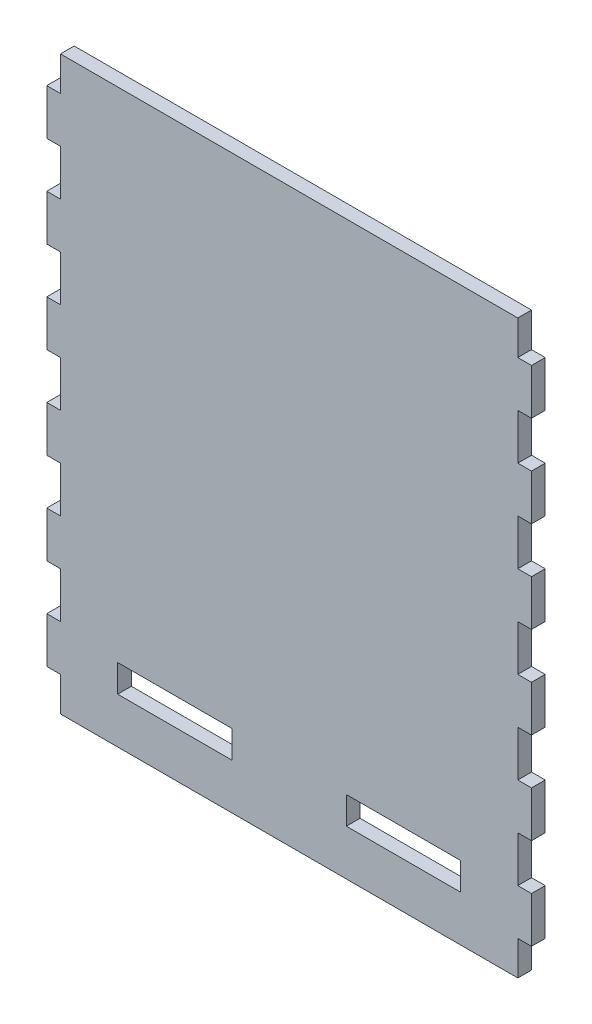
SolidWorks part; units mm, degrees
ref_plane "前视基准面" through (0, 0, 0) normal (0, 0, 1) x (1, 0, 0)
ref_plane "上视基准面" through (0, 0, 0) normal (0, 1, 0) x (1, 0, 0)
ref_plane "右视基准面" through (0, 0, 0) normal (1, 0, 0) x (0, 0, -1)
sketch "草图1" plane through (0, 0, 0) normal (0, 0, 1) x (1, 0, 0)
  line L0 (-118.4309, 110.0336) -> (-118.4309, 90.0336)
  line L1 (-118.4309, 145.0336) -> (81.5691, 145.0336)
  line L2 (-118.4309, 70.0336) -> (-118.4309, 50.0336)
  line L3 (-118.4309, 30.0336) -> (-118.4309, 10.0336)
  line L4 (-118.4309, -9.9664) -> (-118.4309, -29.9664)
  line L5 (-118.4309, -49.9664) -> (-118.4309, -69.9664)
  line L6 (-118.4309, -89.9664) -> (-118.4309, -104.9664)
  line L7 (81.5691, 110.0336) -> (81.5691, 90.0336)
  line L8 (81.5691, 70.0336) -> (81.5691, 50.0336)
  line L9 (81.5691, 30.0336) -> (81.5691, 10.0336)
  line L10 (81.5691, -9.9664) -> (81.5691, -29.9664)
  line L11 (81.5691, -49.9664) -> (81.5691, -69.9664)
  line L12 (81.5691, -89.9664) -> (81.5691, -104.9664)
  line L15 (-43.4309, -84.9664) -> (-93.4309, -84.9664)
  line L16 (-43.4309, -72.9664) -> (-93.4309, -72.9664)
  line L17 (-43.4309, -84.9664) -> (-43.4309, -72.9664)
  line L18 (-93.4309, -72.9664) -> (-93.4309, -84.9664)
  line L20 (6.5691, -84.9664) -> (6.5691, -72.9664)
  line L21 (6.5691, -72.9664) -> (56.5691, -72.9664)
  line L22 (56.5691, -72.9664) -> (56.5691, -84.9664)
  line L23 (-118.4309, -104.9664) -> (81.5691, -104.9664)
  line L24 (56.5691, -84.9664) -> (6.5691, -84.9664)
  line L50 (87.5691, 50.0336) -> (87.5691, 30.0336)
  line L51 (87.5691, 30.0336) -> (81.5691, 30.0336)
  line L53 (81.5691, 50.0336) -> (87.5691, 50.0336)
  line L54 (87.5691, -49.9664) -> (87.5691, -29.9664)
  line L55 (87.5691, 70.0336) -> (81.5691, 70.0336)
  line L57 (81.5691, 90.0336) -> (87.5691, 90.0336)
  line L58 (87.5691, -89.9664) -> (87.5691, -69.9664)
  line L59 (87.5691, 110.0336) -> (81.5691, 110.0336)
  line L61 (81.5691, 130.0336) -> (87.5691, 130.0336)
  line L62 (87.5691, 130.0336) -> (87.5691, 110.0336)
  line L63 (87.5691, 90.0336) -> (87.5691, 70.0336)
  line L64 (81.5691, -89.9664) -> (87.5691, -89.9664)
  line L66 (87.5691, -69.9664) -> (81.5691, -69.9664)
  line L67 (81.5691, -49.9664) -> (87.5691, -49.9664)
  line L69 (87.5691, -29.9664) -> (81.5691, -29.9664)
  line L70 (81.5691, -9.9664) -> (87.5691, -9.9664)
  line L72 (87.5691, 10.0336) -> (81.5691, 10.0336)
  line L73 (87.5691, -9.9664) -> (87.5691, 10.0336)
  line L74 (-124.4309, -9.9664) -> (-124.4309, 10.0336)
  line L75 (-124.4309, 10.0336) -> (-118.4309, 10.0336)
  line L77 (-118.4309, -9.9664) -> (-124.4309, -9.9664)
  line L78 (-124.4309, -29.9664) -> (-118.4309, -29.9664)
  line L80 (-118.4309, -49.9664) -> (-124.4309, -49.9664)
  line L81 (-124.4309, -69.9664) -> (-118.4309, -69.9664)
  line L83 (-118.4309, -89.9664) -> (-124.4309, -89.9664)
  line L84 (-124.4309, 90.0336) -> (-124.4309, 70.0336)
  line L85 (-124.4309, 130.0336) -> (-124.4309, 110.0336)
  line L86 (-118.4309, 130.0336) -> (-124.4309, 130.0336)
  line L88 (-124.4309, 110.0336) -> (-118.4309, 110.0336)
  line L89 (-124.4309, -89.9664) -> (-124.4309, -69.9664)
  line L90 (-118.4309, 90.0336) -> (-124.4309, 90.0336)
  line L92 (-124.4309, 70.0336) -> (-118.4309, 70.0336)
  line L93 (-124.4309, -49.9664) -> (-124.4309, -29.9664)
  line L94 (-118.4309, 50.0336) -> (-124.4309, 50.0336)
  line L96 (-124.4309, 30.0336) -> (-118.4309, 30.0336)
  line L97 (-124.4309, 50.0336) -> (-124.4309, 30.0336)
  line L98 (-118.4309, 145.0336) -> (-118.4309, 130.0336)
  line L99 (81.5691, 145.0336) -> (81.5691, 130.0336)
extrude "凸台-拉伸1" add sketch "草图1" along normal blind 6
